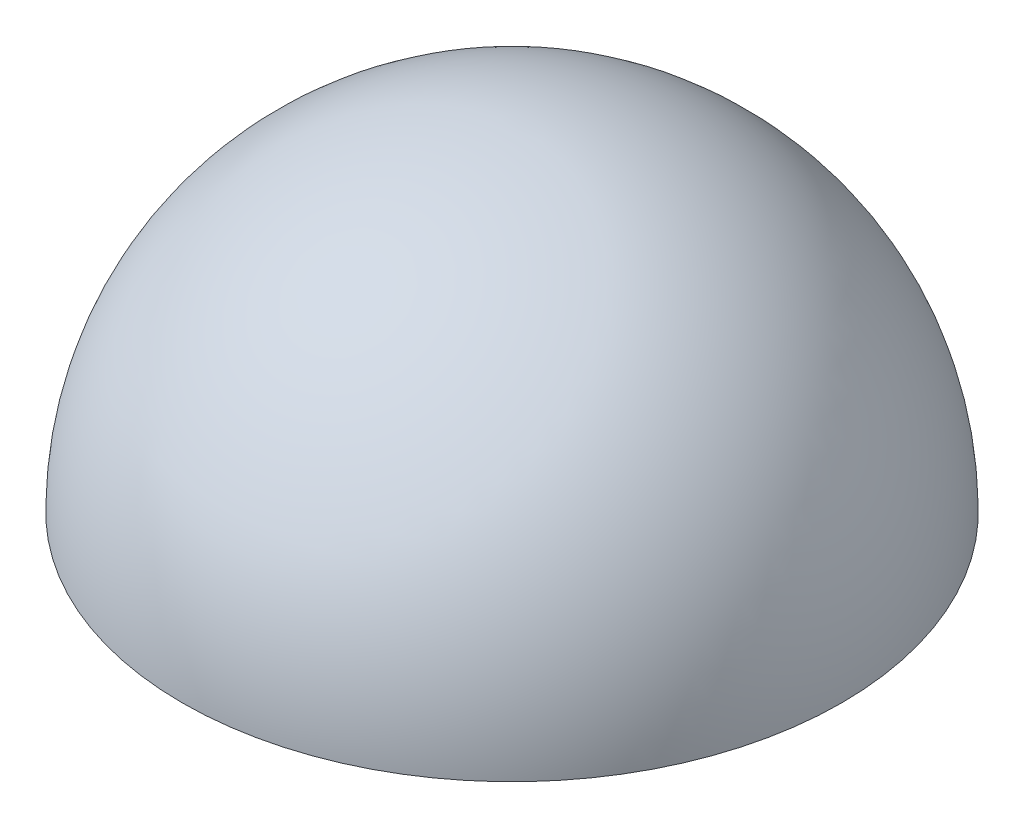
SolidWorks part; units mm, degrees
ref_plane "Plan de face" through (0, 0, 0) normal (0, 0, 1) x (1, 0, 0)
ref_plane "Plan de dessus" through (0, 0, 0) normal (0, 1, 0) x (1, 0, 0)
ref_plane "Plan de droite" through (0, 0, 0) normal (1, 0, 0) x (0, 0, -1)
sketch "Esquisse2" plane through (0, 0, 0) normal (0, 0, 1) x (1, 0, 0)
  line L0 (0, 20.7354) -> (0, -25.6143) construction
  line L1 (16.75, 0) -> (0, 0)
  line L2 (0, 0) -> (0, 16.75)
  arc A0 (0, 16.75) -> (16.75, 0) centre (0, 0) cw
  dimension "D1" = 16.75
revolve "Révolution1" add sketch "Esquisse2" angle 360 about L0
